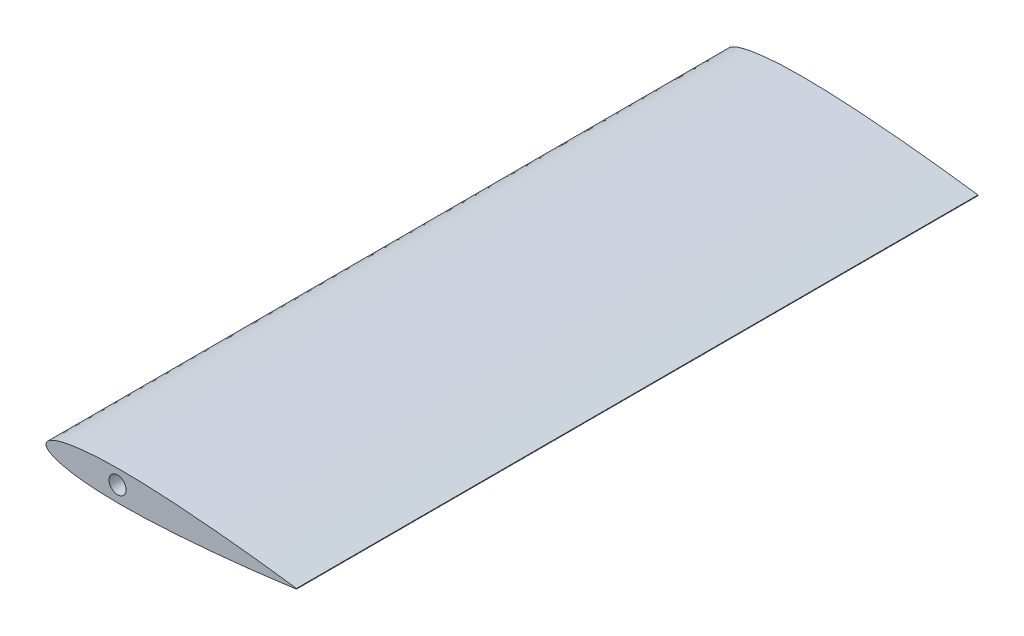
SolidWorks part; units mm, degrees
material "ABS"
ref_plane "Front Plane" through (0, 0, 0) normal (0, 0, 1) x (1, 0, 0)
ref_plane "Top Plane" through (0, 0, 0) normal (0, 1, 0) x (1, 0, 0)
ref_plane "Right Plane" through (0, 0, 0) normal (1, 0, 0) x (0, 0, -1)
curve "Curve1"
  spline degree 3 poles (1, 0.0013, 0) (0.9998, 0.0013, 0) (0.999, 0.0014, 0) (0.9973, 0.0016, 0) (0.9944, 0.002, 0) (0.9903, 0.0026, 0) (0.9851, 0.0033, 0) (0.9788, 0.0042, 0) (0.9713, 0.0052, 0) (0.9627, 0.0064, 0) (0.9531, 0.0077, 0) (0.9424, 0.0091, 0) (0.9307, 0.0106, 0) (0.9179, 0.0122, 0) (0.9042, 0.014, 0) (0.8895, 0.0158, 0) (0.874, 0.0177, 0) (0.8575, 0.0196, 0) (0.8402, 0.0217, 0) (0.8222, 0.0237, 0) (0.8033, 0.0259, 0) (0.7838, 0.028, 0) (0.7636, 0.0302, 0) (0.7428, 0.0324, 0) (0.7214, 0.0345, 0) (0.6995, 0.0367, 0) (0.6772, 0.0388, 0) (0.6544, 0.0409, 0) (0.6313, 0.043, 0) (0.6078, 0.045, 0) (0.5841, 0.0469, 0) (0.5602, 0.0488, 0) (0.5362, 0.0505, 0) (0.5121, 0.0522, 0) (0.4879, 0.0537, 0) (0.4638, 0.0551, 0) (0.4398, 0.0563, 0) (0.4159, 0.0574, 0) (0.3922, 0.0583, 0) (0.3688, 0.0591, 0) (0.3456, 0.0596, 0) (0.3228, 0.0599, 0) (0.3005, 0.0601, 0) (0.2786, 0.06, 0) (0.2572, 0.0596, 0) (0.2364, 0.0591, 0) (0.2162, 0.0583, 0) (0.1966, 0.0572, 0) (0.1778, 0.056, 0) (0.1597, 0.0544, 0) (0.1425, 0.0527, 0) (0.126, 0.0507, 0) (0.1104, 0.0486, 0) (0.0958, 0.0462, 0) (0.0821, 0.0436, 0) (0.0693, 0.0408, 0) (0.0576, 0.0378, 0) (0.0468, 0.0347, 0) (0.0372, 0.0313, 0) (0.0286, 0.0279, 0) (0.0211, 0.0243, 0) (0.0147, 0.0206, 0) (0.0094, 0.0167, 0) (0.0053, 0.0128, 0) (0.0023, 0.0087, 0) (0.0004, 0.0044, 0) (-0.0002, 0, 0) (0.0004, -0.0044, 0) (0.0023, -0.0087, 0) (0.0053, -0.0128, 0) (0.0094, -0.0167, 0) (0.0147, -0.0206, 0) (0.0211, -0.0243, 0) (0.0286, -0.0279, 0) (0.0372, -0.0313, 0) (0.0468, -0.0347, 0) (0.0576, -0.0378, 0) (0.0693, -0.0408, 0) (0.0821, -0.0436, 0) (0.0958, -0.0462, 0) (0.1104, -0.0486, 0) (0.126, -0.0507, 0) (0.1425, -0.0527, 0) (0.1597, -0.0544, 0) (0.1778, -0.056, 0) (0.1966, -0.0572, 0) (0.2162, -0.0583, 0) (0.2364, -0.0591, 0) (0.2572, -0.0596, 0) (0.2786, -0.06, 0) (0.3005, -0.0601, 0) (0.3228, -0.0599, 0) (0.3456, -0.0596, 0) (0.3688, -0.0591, 0) (0.3922, -0.0583, 0) (0.4159, -0.0574, 0) (0.4398, -0.0563, 0) (0.4638, -0.0551, 0) (0.4879, -0.0537, 0) (0.5121, -0.0522, 0) (0.5362, -0.0505, 0) (0.5602, -0.0488, 0) (0.5841, -0.0469, 0) (0.6078, -0.045, 0) (0.6313, -0.043, 0) (0.6544, -0.0409, 0) (0.6772, -0.0388, 0) (0.6995, -0.0367, 0) (0.7214, -0.0345, 0) (0.7428, -0.0324, 0) (0.7636, -0.0302, 0) (0.7838, -0.028, 0) (0.8033, -0.0259, 0) (0.8222, -0.0237, 0) (0.8402, -0.0217, 0) (0.8575, -0.0196, 0) (0.874, -0.0177, 0) (0.8895, -0.0158, 0) (0.9042, -0.014, 0) (0.9179, -0.0122, 0) (0.9307, -0.0106, 0) (0.9424, -0.0091, 0) (0.9531, -0.0077, 0) (0.9627, -0.0064, 0) (0.9713, -0.0052, 0) (0.9788, -0.0042, 0) (0.9851, -0.0033, 0) (0.9903, -0.0026, 0) (0.9944, -0.002, 0) (0.9973, -0.0016, 0) (0.999, -0.0014, 0) (0.9998, -0.0013, 0) (1, -0.0013, 0) knots 0 0 0 0 0.000289 0.001156 0.002598 0.004612 0.007194 0.010336 0.014031 0.018272 0.023046 0.028343 0.03415 0.040454 0.047238 0.054489 0.062187 0.070314 0.078852 0.08778 0.097078 0.106722 0.116691 0.126961 0.137507 0.148306 0.159331 0.170556 0.181957 0.193504 0.205171 0.216932 0.228758 0.240621 0.252495 0.26435 0.276161 0.287898 0.299536 0.311047 0.322405 0.333584 0.344559 0.355306 0.3658 0.376018 0.385937 0.395538 0.404798 0.413699 0.422221 0.430349 0.438066 0.445357 0.452209 0.458612 0.464554 0.47003 0.475035 0.479569 0.483637 0.48725 0.490431 0.493219 0.495674 0.497891 0.5 0.502109 0.504326 0.506781 0.509569 0.51275 0.516363 0.520431 0.524965 0.52997 0.535446 0.541388 0.547791 0.554643 0.561934 0.569651 0.577779 0.586301 0.595202 0.604462 0.614063 0.623982 0.6342 0.644694 0.655441 0.666416 0.677595 0.688953 0.700464 0.712102 0.723839 0.73565 0.747505 0.759379 0.771242 0.783068 0.794829 0.806496 0.818043 0.829444 0.840669 0.851694 0.862493 0.873039 0.883309 0.893278 0.902922 0.91222 0.921148 0.929686 0.937813 0.945511 0.952762 0.959546 0.96585 0.971657 0.976954 0.981728 0.985969 0.989664 0.992806 0.995388 0.997402 0.998844 0.999711 1 1 1 1
sketch "Sketch7" plane through (0, 0, 0) normal (0, 0, 1) x (1, 0, 0)
  line L0 (1, -0.1046) -> (1, -0.0305)
  spline S1 degree 3 poles (1, -0.0305) (0.4391, 0.0483) (-1.6744, 0.334) (-4.6175, 0.6842) (-8.1327, 1.0467) (-10.798, 1.2847) (-13.3462, 1.4715) (-15.4585, 1.5943) (-17.5341, 1.6757) (-19.5296, 1.7066) (-21.2181, 1.6828) (-22.5985, 1.6201) (-23.6814, 1.5397) (-24.6714, 1.4322) (-25.4327, 1.3183) (-25.9877, 1.2132) (-26.3625, 1.1311) (-26.7078, 1.0436) (-27.0228, 0.9512) (-27.3068, 0.8541) (-27.5593, 0.7526) (-27.7796, 0.6472) (-27.9675, 0.5378) (-28.1226, 0.4249) (-28.2448, 0.3081) (-28.3336, 0.1871) (-28.3879, 0.0614) (-28.4059, -0.0675) (-28.3879, -0.1965) (-28.3336, -0.3222) (-28.2448, -0.4432) (-28.1226, -0.5599) (-27.9675, -0.6729) (-27.7796, -0.7822) (-27.5593, -0.8877) (-27.3068, -0.9892) (-27.0228, -1.0863) (-26.7078, -1.1787) (-26.3625, -1.2662) (-25.8453, -1.3794) (-25.1286, -1.5039) (-24.1886, -1.6243) (-22.9535, -1.7363) (-21.4032, -1.8152) (-19.2995, -1.8449) (-17.0681, -1.7988) (-14.7563, -1.6926) (-12.6416, -1.5581) (-10.3295, -1.3786) (-8.3035, -1.1944) (-5.6924, -0.9326) (-3.1098, -0.6438) (-0.6443, -0.3306) (0.587, -0.1624) (0.9486, -0.1118) (1, -0.1046) knots 0 0 0 0 0.028343 0.106722 0.148306 0.205171 0.240621 0.276161 0.311047 0.344559 0.376018 0.395538 0.413699 0.430349 0.445357 0.452209 0.458612 0.464554 0.47003 0.475035 0.479569 0.483637 0.48725 0.490431 0.493219 0.495674 0.497891 0.5 0.502109 0.504326 0.506781 0.509569 0.51275 0.516363 0.520431 0.524965 0.52997 0.535446 0.541388 0.547791 0.561934 0.577779 0.595202 0.623982 0.655441 0.700464 0.73565 0.771242 0.806496 0.851694 0.873039 0.937813 0.981728 0.997402 1 1 1 1
extrude "Boss-Extrude4" add sketch "Sketch7" along normal blind 80
sketch "Sketch8" plane through (0, 0, 80) normal (0, 0, 1) x (1, 0, 0)
  line L0 (1, -0.1046) -> (1, -0.0305) construction
  circle A0 centre (-20, 0) radius 1
  dimension "D1" = 21
extrude "Cut-Extrude3" cut sketch "Sketch8" against normal through all
